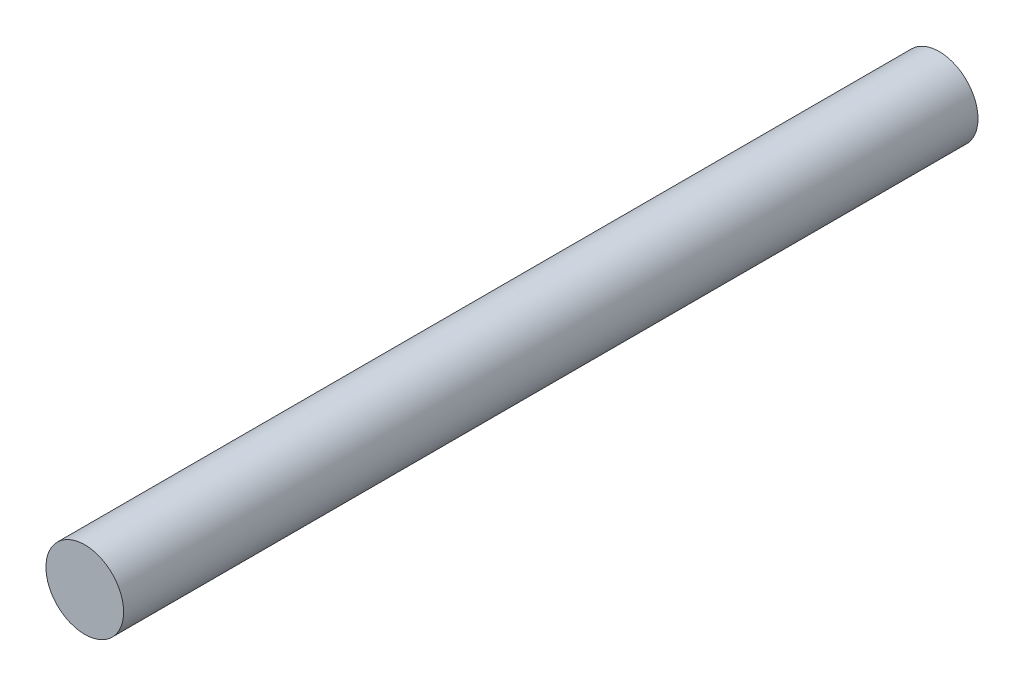
SolidWorks part; units mm, degrees
material "Hexcel AS4C (3000 Filaments)"
ref_plane "Front" through (0, 0, 0) normal (0, 0, 1) x (1, 0, 0)
ref_plane "Top" through (0, 0, 0) normal (0, 1, 0) x (1, 0, 0)
ref_plane "Right" through (0, 0, 0) normal (1, 0, 0) x (0, 0, -1)
sketch "Sketch1" plane through (0, 0, 0) normal (0, 0, 1) x (1, 0, 0)
  circle A0 centre (0, 0) radius 3.175
  dimension "D1" = 6.35
extrude "Boss-Extrude1" add sketch "Sketch1" along normal blind 69.85
equation "\"truss_member_od\" = .25in"
equation "\"truss_member_id\" = 0in"
equation "\"truss_member_L1\" = 2.75in"
equation "\"D1@Sketch1\"=\"truss_member_od\""
equation "\"D1@Boss-Extrude1\"=\"truss_member_L1\""
